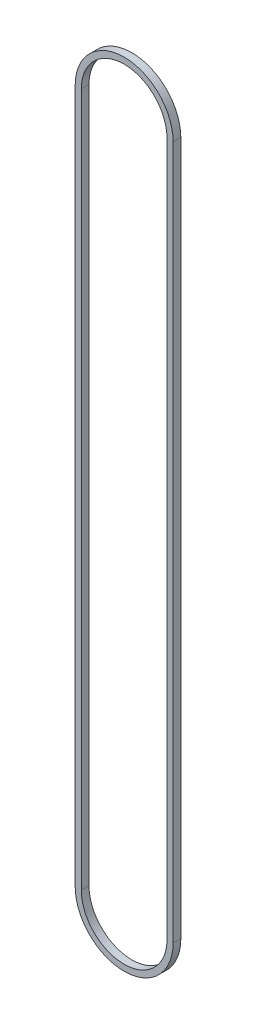
SolidWorks part; units mm, degrees
material "POLYURETHANE (11671)"
ref_plane "Front Plane" through (0, 0, 0) normal (0, 0, 1) x (1, 0, 0)
ref_plane "Top Plane" through (0, 0, 0) normal (0, 1, 0) x (1, 0, 0)
ref_plane "Right Plane" through (0, 0, 0) normal (1, 0, 0) x (0, 0, -1)
sketch "Sketch1" plane through (0, 0, 0) normal (0, 0, 1) x (1, 0, 0)
  line L0 (0, 850) -> (0, -850) construction
  line L1 (105, 850) -> (105, -850)
  line L2 (-105, 850) -> (-105, -850)
  line L3 (120, 850) -> (120, -850)
  line L4 (-120, 850) -> (-120, -850)
  arc A0 (105, 850) -> (-105, 850) centre (0, 850) ccw
  arc A1 (-105, -850) -> (105, -850) centre (0, -850) ccw
  arc A2 (-120, -850) -> (120, -850) centre (0, -850) ccw
  arc A3 (120, 850) -> (-120, 850) centre (0, 850) ccw
  point P3 (0, 0)
  point P8 (0, 0)
  point P9 (0, 0)
  dimension "D2" = 105
  dimension "D1" = 1700
  dimension "D3" = 15
extrude "Boss-Extrude1" add sketch "Sketch1" along normal blind 18.82
